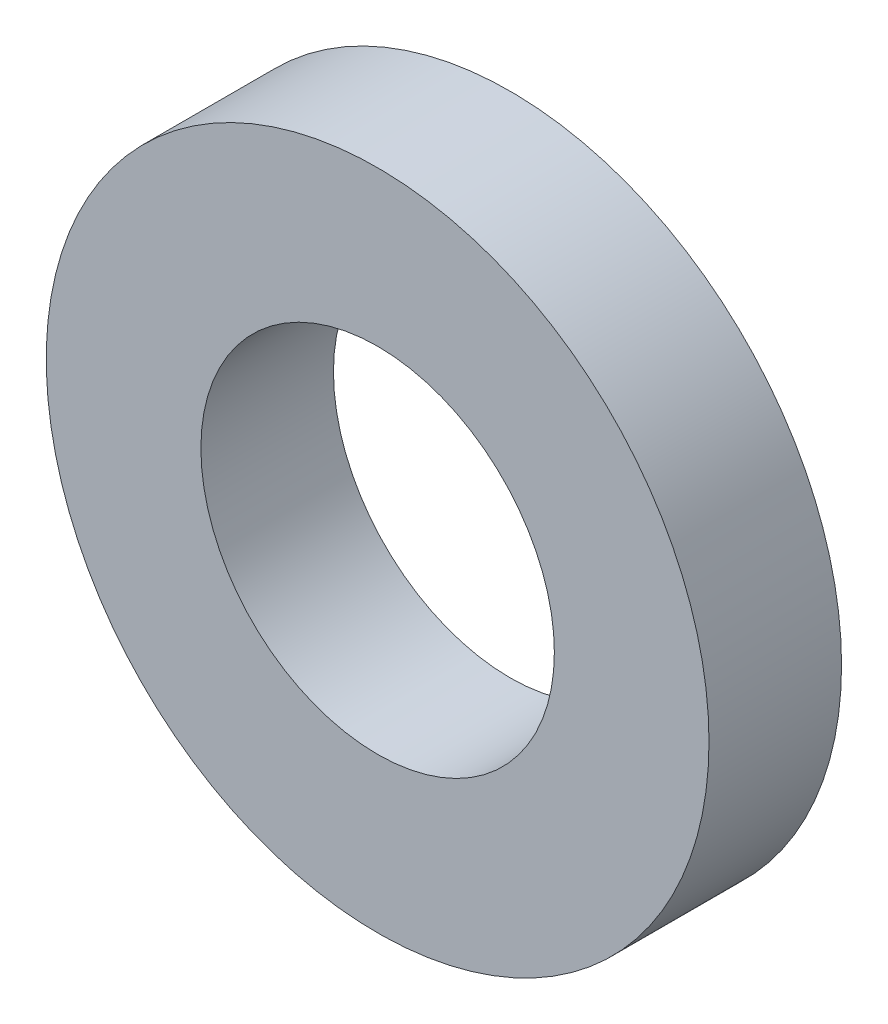
SolidWorks part; units mm, degrees
ref_plane "Top Plane" through (0, 0, 0) normal (0, 0, 1) x (1, 0, 0)
ref_plane "Right Plane" through (0, 0, 0) normal (0, 1, 0) x (1, 0, 0)
ref_plane "Front Plane" through (0, 0, 0) normal (1, 0, 0) x (0, 0, -1)
sketch "Sketch1" plane through (0, 0, 0) normal (0, 0, 1) x (1, 0, 0)
  circle A0 centre (0, 0) radius 4
  circle A1 centre (0, 0) radius 7.5
  dimension "D1" = 15
  dimension "D2" = 8
extrude "Boss-Extrude1" add sketch "Sketch1" along normal mid plane 3
